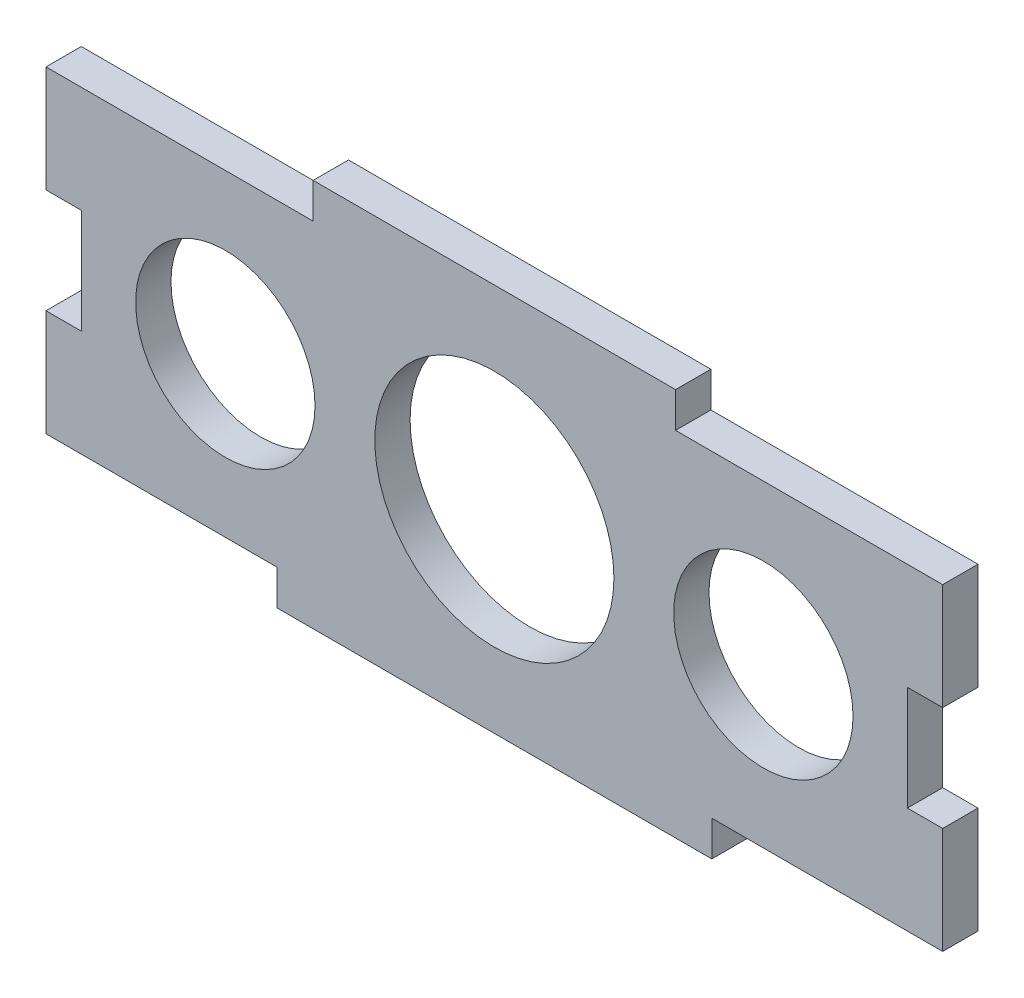
SolidWorks part; units mm, degrees
material "Acrylic (Medium-high impact)"
ref_plane "Front Plane" through (0, 0, 0) normal (0, 0, 1) x (1, 0, 0)
ref_plane "Top Plane" through (0, 0, 0) normal (0, 1, 0) x (1, 0, 0)
ref_plane "Right Plane" through (0, 0, 0) normal (1, 0, 0) x (0, 0, -1)
sketch "스케치1" plane through (0, 0, 0) normal (0, 0, 1) x (1, 0, 0)
  line L1 (-38.1, -15) -> (38.1, -15)
  line L2 (-38.1, -15) -> (-38.1, 15)
  line L3 (-38.1, 15) -> (38.1, 15)
  line L4 (38.1, -15) -> (38.1, 15)
  line L5 (-38.1, -15) -> (38.1, 15) construction
  line L6 (-38.1, 15) -> (38.1, -15) construction
  line L7 (-32.0618, -12) -> (21.075, -12) construction
  line L8 (-32.0618, -12) -> (-32.0618, -8.0122) construction
  line L9 (-32.0618, -8.0122) -> (21.075, -8.0122) construction
  line L10 (21.075, -12) -> (21.075, -8.0122) construction
  line L11 (-32.0618, -12) -> (21.075, -8.0122) construction
  line L12 (-32.0618, -8.0122) -> (21.075, -12) construction
  line L14 (8.4639, -8.0122) -> (17.4047, -8.0122) construction
  line L15 (8.4639, -8.0122) -> (8.4639, 3.0876) construction
  line L16 (8.4639, 3.0876) -> (17.4047, 3.0876) construction
  line L17 (17.4047, -8.0122) -> (17.4047, 3.0876) construction
  line L18 (8.4639, -8.0122) -> (17.4047, 3.0876) construction
  line L19 (8.4639, 3.0876) -> (17.4047, -8.0122) construction
  line L20 (-23.0575, -8.0122) -> (-10.9036, -8.0122) construction
  line L21 (-23.0575, -8.0122) -> (-23.0575, 2.732) construction
  line L22 (-23.0575, 2.732) -> (-10.9036, 2.732) construction
  line L23 (-10.9036, -8.0122) -> (-10.9036, 2.732) construction
  line L24 (-23.0575, -8.0122) -> (-10.9036, 2.732) construction
  line L25 (-23.0575, 2.732) -> (-10.9036, -8.0122) construction
  point P0 (0, 0)
  point P6 (-5.4934, -10.0061)
  point P17 (12.9343, -2.4623)
  point P22 (-16.9806, -2.6401)
  dimension "D1" = 76.2
  dimension "D2" = 53.1368
  dimension "D3" = 3.9878
  dimension "D4" = 3
  dimension "D5" = 8.9408
  dimension "D6" = 30
  dimension "D7" = 11.0998
  dimension "D8" = 10.7442
  dimension "D9" = 12.1539
  dimension "D10" = 19.3675
  dimension "D11" = 9.0043
  dimension "D12" = 17.025
extrude "보스-돌출1" add sketch "스케치1" along normal blind 3
sketch "스케치2" plane through (0, 0, 3) normal (0, 0, 1) x (1, 0, 0)
  line L0 (-38.1, -15) -> (38.1, -15) construction
  line L1 (-38.1, -15) -> (-18.4785, -15)
  line L2 (-38.1, -15) -> (-38.1, -12)
  line L3 (-38.1, -12) -> (-18.4785, -12)
  line L4 (-18.4785, -15) -> (-18.4785, -12)
  line L5 (-38.1, -15) -> (-18.4785, -12) construction
  line L6 (-38.1, -12) -> (-18.4785, -15) construction
  line L7 (18.4785, -15) -> (38.1, -15)
  line L8 (18.4785, -15) -> (18.4785, -12)
  line L9 (18.4785, -12) -> (38.1, -12)
  line L10 (38.1, -15) -> (38.1, -12)
  line L11 (18.4785, -15) -> (38.1, -12) construction
  line L12 (18.4785, -12) -> (38.1, -15) construction
  line L13 (38.1, -15) -> (38.1, 15) construction
  line L14 (18.4785, -12) -> (-18.4785, -12) construction
  point P4 (-28.2892, -13.5)
  point P10 (28.2892, -13.5)
  dimension "D1" = 36.957
  dimension "D2" = 3
extrude "컷-돌출1" cut sketch "스케치2" against normal up to surface (3 mm away) up to face at (0, 0, 0)
sketch "스케치3" plane through (0, 0, 3) normal (0, 0, 1) x (1, 0, 0)
  line L0 (-38.1, 15) -> (-38.1, -12) construction
  line L1 (-38.1, -2.945) -> (-35.1, -2.945)
  line L2 (-38.1, -2.945) -> (-38.1, 5.945)
  line L3 (-38.1, 5.945) -> (-35.1, 5.945)
  line L4 (-35.1, -2.945) -> (-35.1, 5.945)
  line L5 (-38.1, -2.945) -> (-35.1, 5.945) construction
  line L6 (-38.1, 5.945) -> (-35.1, -2.945) construction
  line L7 (38.1, -12) -> (38.1, 15) construction
  line L8 (38.1, 5.945) -> (35.1, 5.945)
  line L9 (38.1, 5.945) -> (38.1, -2.945)
  line L10 (38.1, -2.945) -> (35.1, -2.945)
  line L11 (35.1, 5.945) -> (35.1, -2.945)
  line L12 (38.1, 5.945) -> (35.1, -2.945) construction
  line L13 (38.1, -2.945) -> (35.1, 5.945) construction
  line L14 (38.1, 1.5) -> (-38.1, 1.5) construction
  point P4 (-36.6, 1.5)
  point P11 (36.6, 1.5)
  dimension "D1" = 8.89
  dimension "D2" = 3
extrude "컷-돌출2" cut sketch "스케치3" against normal up to surface (3 mm away) up to face at (0, -6, 0)
sketch "스케치4" plane through (0, 0, 3) normal (0, 0, 1) x (1, 0, 0)
  line L0 (38.1, 15) -> (-38.1, 15) construction
  line L1 (-15.3987, 18) -> (15.3988, 18)
  line L2 (-15.3987, 18) -> (-15.3987, 15)
  line L3 (-15.3987, 15) -> (15.3988, 15)
  line L4 (15.3988, 18) -> (15.3988, 15)
  line L5 (-15.3987, 18) -> (15.3988, 15) construction
  line L6 (-15.3987, 15) -> (15.3988, 18) construction
  line L7 (0, 16.5) -> (0, 0) construction
  point P0 (0, 16.5)
  dimension "D1" = 30.7975
  dimension "D2" = 3
extrude "보스-돌출2" add sketch "스케치4" against normal up to surface (3 mm away) up to face at (0, -2.25, 0)
sketch "스케치5" plane through (0, 0, 3) normal (0, 0, 1) x (1, 0, 0)
  line L0 (38.1, -12) -> (18.4785, -12) construction
  line L1 (35.1, 5.945) -> (35.1, -2.945) construction
  line L2 (21.13, 0.7) -> (35.1, 0.7) construction
  line L3 (21.13, 0.7) -> (21.13, -12) construction
  line L4 (21.13, -12) -> (35.1, -12) construction
  line L5 (35.1, 0.7) -> (35.1, -12) construction
  line L6 (21.13, 0.7) -> (35.1, -12) construction
  line L7 (21.13, -12) -> (35.1, 0.7) construction
  circle A0 centre (28.115, -5.65) radius 2.75
  dimension "D1" = 5.5
  dimension "D2" = 13.97
  dimension "D3" = 12.7
extrude "컷-돌출3" [suppressed] cut sketch "스케치5" against normal up to surface (3 mm away)
sketch "스케치6" plane through (0, 0, 3) normal (0, 0, 1) x (1, 0, 0)
  line L0 (-35.1, 1.5) -> (35.1, 1.5) construction
  line L1 (-35.1, -2.945) -> (-35.1, 5.945) construction
  line L2 (35.1, 5.945) -> (35.1, -2.945) construction
  circle A0 centre (0, 1.5) radius 10.16
  circle A1 centre (-22.86, 1.5) radius 7.62
  circle A2 centre (22.86, 1.5) radius 7.62
  dimension "D1" = 20.32
  dimension "D2" = 15.24
  dimension ".6" = 15.24
  dimension "D4" = 22.86
  dimension "D5" = 22.86
extrude "컷-돌출4" cut sketch "스케치6" against normal up to surface (3 mm away) up to face at (0, 1.5, 0)
